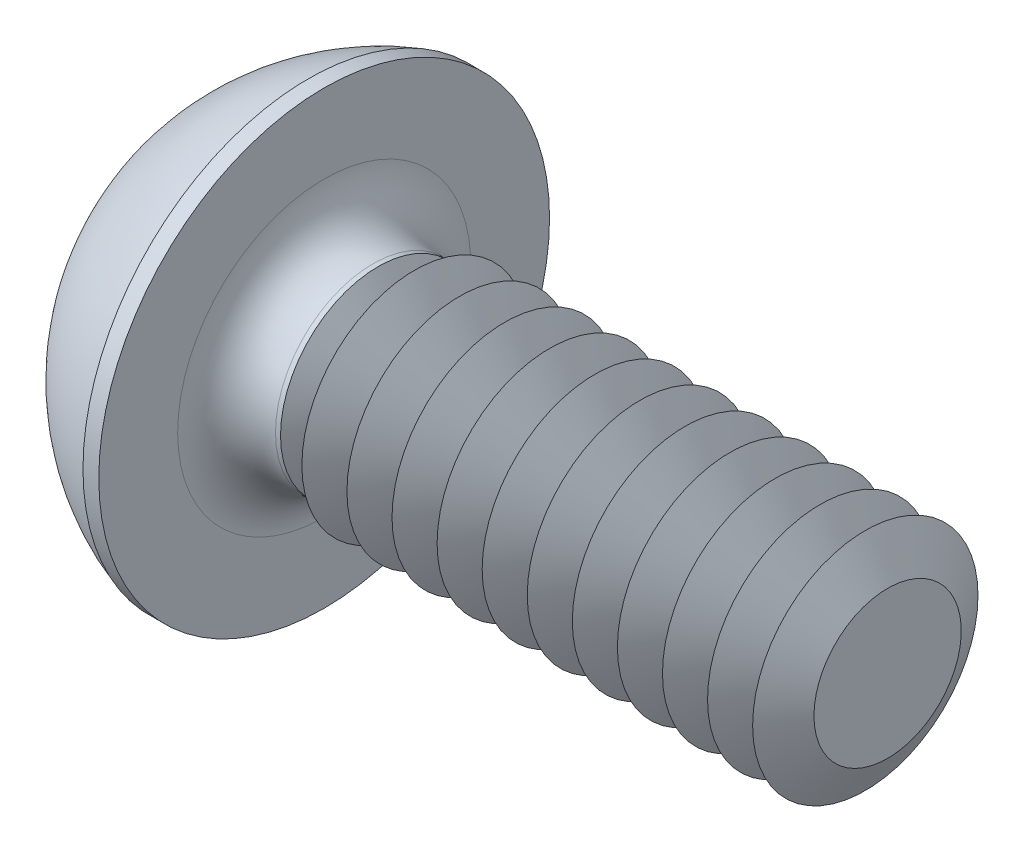
SolidWorks part; units mm, degrees
revolve "基体-旋转" add sketch "草图2" angle 360 about L0
sketch "草图2" plane through (0, 0, 0) normal (0, 0, 1) x (1, 0, 0)
  line L0 (-1.3318, 0) -> (6.5885, 0) construction
  line L1 (0, 0) -> (6.6, 0)
  line L2 (6.6, 0) -> (6.6, 1)
  line L3 (6.6, 1) -> (2.4, 1)
  line L4 (2.4, 1) -> (2.266, 0.866)
  line L5 (2.266, 0.866) -> (2.034, 0.866)
  line L6 (1.6, 1.3) -> (1.6, 2)
  line L7 (1.6, 2) -> (1.4597, 2)
  arc A0 (1.6, 1.3) -> (2.034, 0.866) centre (2.034, 1.3) ccw
  arc A1 (0, 0) -> (1.4597, 2) centre (2.1, 0) cw
  dimension "D3" = 2.1
  dimension "dk" = 4
  dimension "d" = 2
  dimension "l" = 5
  dimension "a" = 0.8
  dimension "D1" = 45
  dimension "D2" = 1.732
  dimension "da" = 2.6
  dimension "k" = 1.6
material "钢"
ref_plane "前视" through (0, 0, 0) normal (0, 0, 1) x (1, 0, 0)
ref_plane "上视" through (0, 0, 0) normal (0, 1, 0) x (1, 0, 0)
ref_plane "右视" through (0, 0, 0) normal (1, 0, 0) x (0, 0, -1)
sketch "尺寸草图" plane through (0, 0, 0) normal (0, 0, 1) x (1, 0, 0)
  line L0 (0, 0) -> (5, 0)
  line L1 (0, 0) -> (0, 4)
  line L2 (5, 0) -> (5, 2.6)
  point P5 (0, 2)
  point P6 (4.6, 0)
  point P7 (0.8, 0)
  point P8 (1.6, 0)
  point P9 (2.9, 0)
  point P10 (1.9, 0)
  point P11 (3.8, 0)
  dimension "dk" = 4
  dimension "d" = 2
  dimension "l" = 5
  dimension "a" = 0.8
  dimension "da" = 2.6
  dimension "k" = 1.6
  dimension "P" = 0.4
  dimension "rf" = 2.1
  dimension "m" = 1.9
  dimension "h" = 1.2
sketch "草图3" plane through (0, 0, 0) normal (0, 0, 1) x (1, 0, 0)
  line L0 (6.4022, 1) -> (6.8022, 1)
  line L1 (6.8022, 1) -> (6.6, 0.6536)
  line L2 (6.6, 0.6536) -> (6.4022, 1)
  line L3 (6.6, 1) -> (2.4, 1) construction
  line L4 (6.6, -1) -> (6.6, 1) construction
  line L5 (-0.2428, 0) -> (7.1644, 0) construction
  line L6 (-1.3318, 0) -> (6.5885, 0) construction
  dimension "P" = 0.4
  dimension "D1" = 0.3464
  dimension "D2" = 60
revolve "切除-旋转1" cut sketch "草图3" angle 360 about L5
sketch "草图5" plane through (0, 0, 0) normal (1, 0, 0) x (0, 0, -1)
  line L1 (0.2, 0.95) -> (-0.2, 0.95)
  line L2 (0.2, 0.95) -> (0.2, -0.95)
  line L3 (0.2, -0.95) -> (-0.2, -0.95)
  line L4 (-0.2, 0.95) -> (-0.2, -0.95)
  point P4 (0.2, 0)
  point P5 (0, 0.95)
  dimension "m" = 1.9
  dimension "D1" = 0.4
ref_plane "基准面1" through (1.2, 0, 0) normal (1, 0, 0) x (0, 0, -1)
pattern_linear "阵列(线性)1" count 12 spacing 0.4 along (-1, 0, 0) of "切除-旋转1"
sketch "草图6" plane through (1.2, 0, 0) normal (1, 0, 0) x (0, 0, -1)
  point P0 (0, 0)
loft "切除-放样1" cut profiles "草图6", "草图5"
ref_plane "基准面2" through (0, 0, 0) normal (0, -0.7071, 0.7071) x (1, 0, 0)
mirror "镜向1" about plane through (0, 0, 0) normal (0, -0.7071, 0.7071) of "切除-放样1"
equation "\"l@草图2\" = \"l@尺寸草图\""
equation "\"dk@草图2\" = \"dk@尺寸草图\""
equation "\"k@草图2\" = \"k@尺寸草图\""
equation "\"D2@草图2\" = \"d@尺寸草图\"*0.866"
equation "\"a@草图2\" = \"a@尺寸草图\""
equation "\"D3@草图2\" = \"rf@尺寸草图\""
equation "\"d@草图2\" = \"d@尺寸草图\""
equation "\"da@草图2\" = \"da@尺寸草图\""
equation "\"D2\"= \"d@尺寸草图\" * 0.866"
equation "\"D1\"= \"l@尺寸草图\" - \"a@尺寸草图\""
equation "\"P@草图3\" = \"P@尺寸草图\""
equation "\"D1@草图3\" = \"P@尺寸草图\"*0.866"
equation "\"h@基准面1\" = \"h@尺寸草图\""
equation "\"D1@草图5\" = \"P@尺寸草图\""
equation "\"m@草图5\" = \"m@尺寸草图\""
equation "\"D3@阵列(线性)1\" = \"P@尺寸草图\""
equation "\"D1@阵列(线性)1\" = (\"l@尺寸草图\"-\"a@尺寸草图\")/\"P@尺寸草图\"+1"
